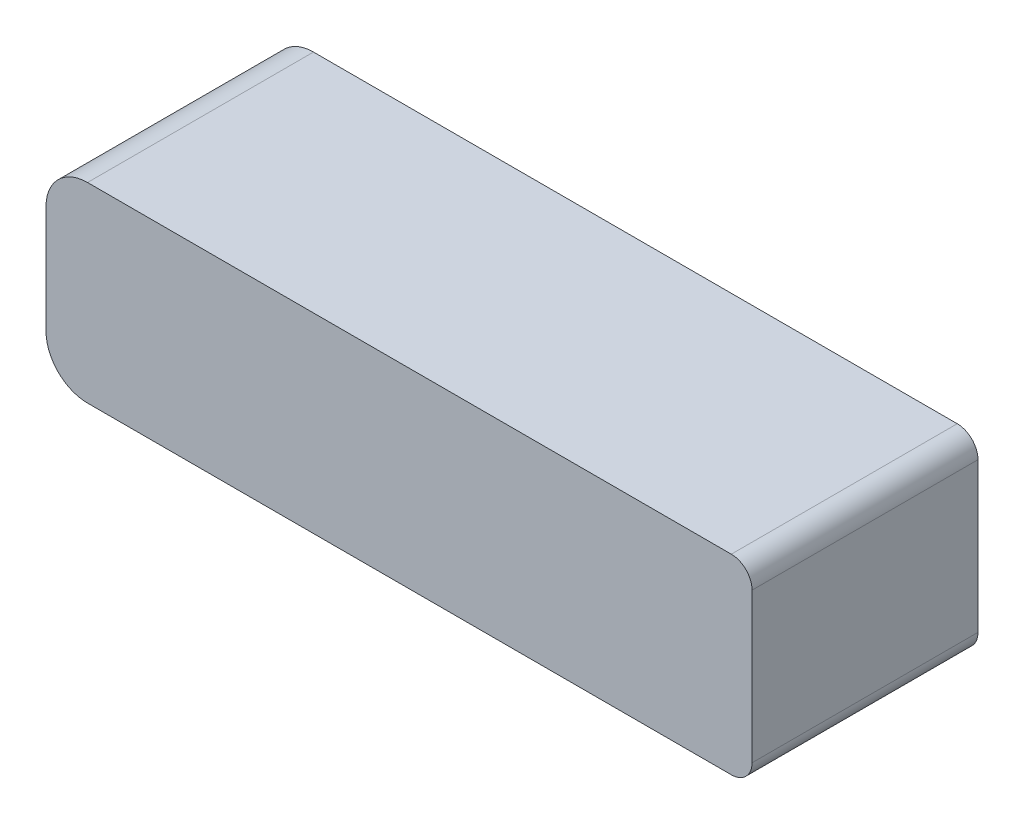
SolidWorks part; units mm, degrees
ref_plane "Front Plane" through (0, 0, 0) normal (0, 0, 1) x (1, 0, 0)
ref_plane "Top Plane" through (0, 0, 0) normal (0, 1, 0) x (1, 0, 0)
ref_plane "Right Plane" through (0, 0, 0) normal (1, 0, 0) x (0, 0, -1)
sketch "Sketch1" plane through (0, 0, 0) normal (0, 1, 0) x (1, 0, 0)
  line L0 (-53.975, 17.272) -> (53.975, 17.272)
  line L1 (53.975, 17.272) -> (53.975, -17.272)
  line L2 (53.975, -17.272) -> (-53.975, -17.272)
  line L3 (-53.975, -17.272) -> (-53.975, 17.272)
  point P2 (0, 17.272)
  point P5 (-53.975, 0)
  dimension "D1" = 107.95
  dimension "D2" = 34.544
extrude "Boss-Extrude1" add sketch "Sketch1" along normal blind 14.605 and the other way blind 14.605
sketch "Sketch2" plane through (0, 14.605, 0) normal (0, 1, 0) x (1, 0, 0)
  text T0 "High Discharge Battery"
fillet "Fillet1" radius 3.175 2 edges at (53.975, -14.605, 0) (53.975, 14.605, 0)
fillet "Fillet2" radius 6.35 2 edges at (-53.975, -14.605, 0) (-53.975, 14.605, 0)
